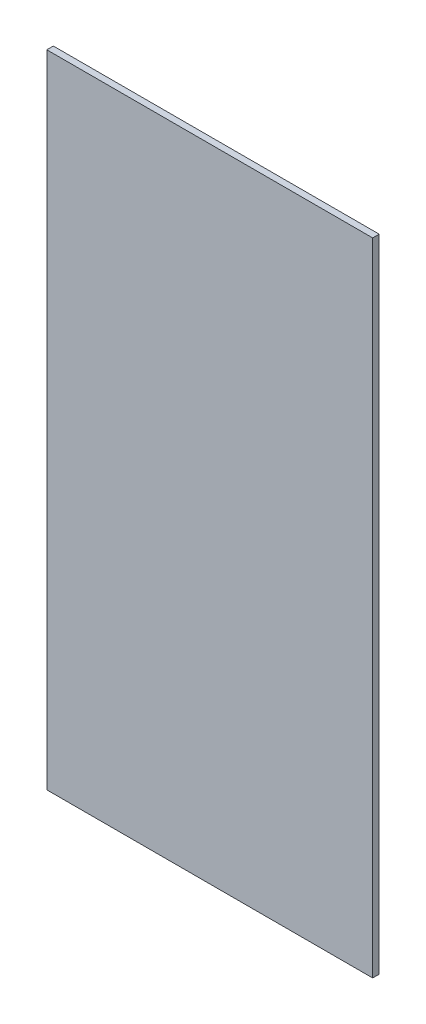
SolidWorks part; units mm, degrees
material "Pine"
ref_plane "Front Plane" through (0, 0, 0) normal (0, 0, 1) x (1, 0, 0)
ref_plane "Top Plane" through (0, 0, 0) normal (0, 1, 0) x (1, 0, 0)
ref_plane "Right Plane" through (0, 0, 0) normal (1, 0, 0) x (0, 0, -1)
sketch "Sketch1" plane through (0, 0, 0) normal (0, 0, 1) x (1, 0, 0)
  line L1 (-75, -147.5) -> (75, -147.5)
  line L2 (-75, -147.5) -> (-75, 147.5)
  line L3 (-75, 147.5) -> (75, 147.5)
  line L4 (75, -147.5) -> (75, 147.5)
  dimension "D1" = 150
  dimension "D2" = 75
  dimension "D3" = 295
  dimension "D4" = 147.5
extrude "Boss-Extrude1" add sketch "Sketch1" along normal blind 3
